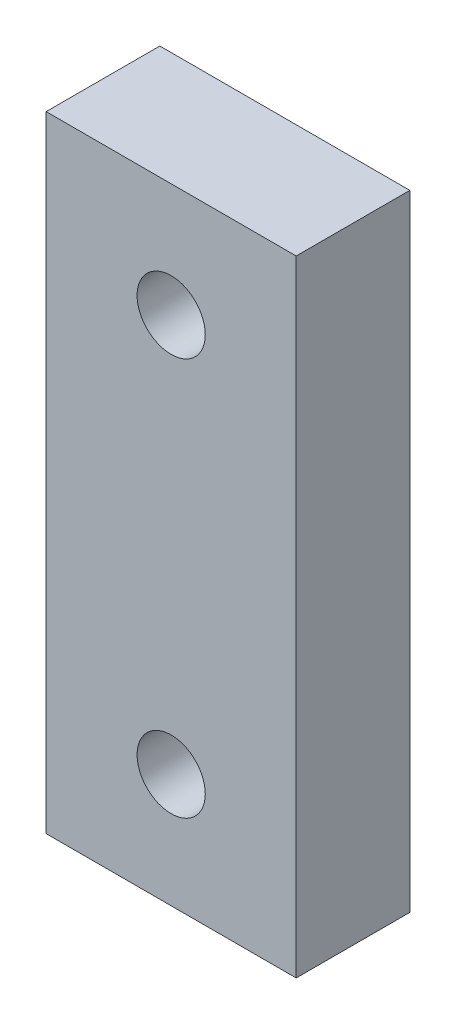
SolidWorks part; units mm, degrees
ref_plane "Front Plane" through (0, 0, 0) normal (0, 0, 1) x (1, 0, 0)
ref_plane "Top Plane" through (0, 0, 0) normal (0, 1, 0) x (1, 0, 0)
ref_plane "Right Plane" through (0, 0, 0) normal (1, 0, 0) x (0, 0, -1)
sketch "Sketch1" plane through (0, 0, 0) normal (0, 0, 1) x (1, 0, 0)
  line L1 (-5.5, 13.755) -> (5.5, 13.755)
  line L2 (-5.5, 13.755) -> (-5.5, -13.755)
  line L3 (-5.5, -13.755) -> (5.5, -13.755)
  line L4 (5.5, 13.755) -> (5.5, -13.755)
  line L5 (-5.5, 13.755) -> (5.5, -13.755) construction
  line L6 (-5.5, -13.755) -> (5.5, 13.755) construction
  point P0 (0, 0)
  dimension "D1" = 27.51
  dimension "D2" = 5.5
extrude "Boss-Extrude2" add sketch "Sketch1" along normal blind 5
sketch "Sketch3" plane through (0, 0, 5) normal (0, 0, 1) x (1, 0, 0)
  line L0 (-5.5, 10.755) -> (5.5, 10.755) construction
  line L1 (-5.5, 13.755) -> (-5.5, -13.755) construction
  line L2 (5.5, -13.755) -> (5.5, 13.755) construction
  line L3 (-5.5, -10.755) -> (5.5, -10.755) construction
  line L4 (0, 13.755) -> (0, -13.755) construction
  line L5 (5.5, 13.755) -> (-5.5, 13.755) construction
  line L6 (-5.5, -13.755) -> (5.5, -13.755) construction
  line L7 (0, 7.255) -> (0, -7.245)
  line L8 (0, 10.255) -> (0, 10.755)
  line L9 (0, -10.245) -> (0, -10.755)
  circle A0 centre (0, 8.755) radius 1.5
  circle A2 centre (0, -8.745) radius 1.5
  line M7 (5.5, -13.755) -> (5.5, 13.755)
  dimension "D3" = 14.5
  dimension "D4" = 3
  dimension "D5" = 3
  dimension "D6" = 0.5
  dimension "D1" = 3
  dimension "D2" = 3
  dimension "D7" = 0.51
extrude "Cut-Extrude1" cut sketch "Sketch3" against normal blind 5 contours A0 | A2 M7
